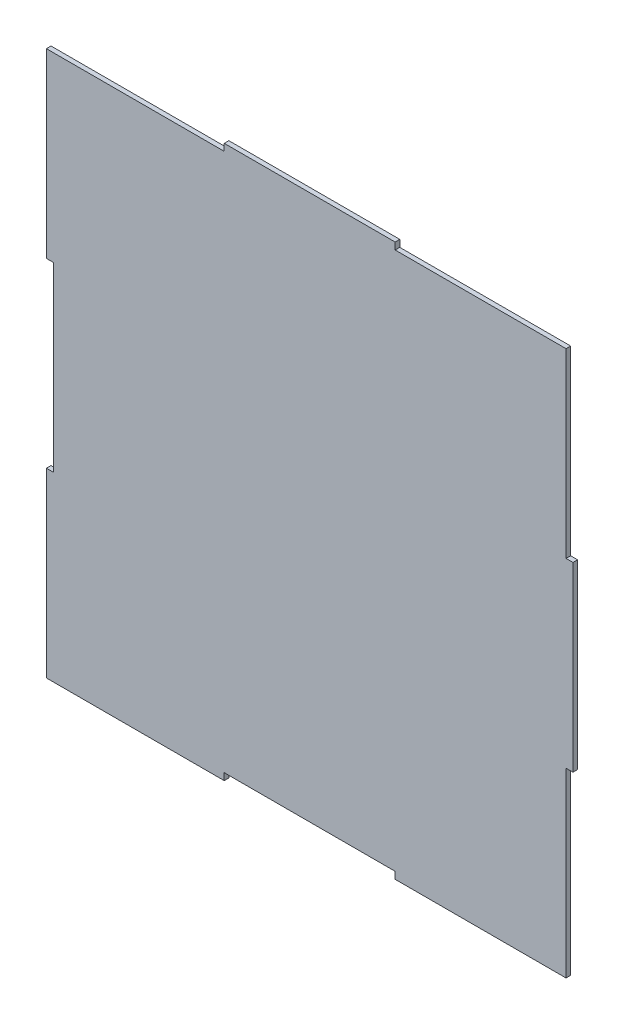
SolidWorks part; units mm, degrees
ref_plane "Front Plane" through (0, 0, 0) normal (0, 0, 1) x (1, 0, 0)
ref_plane "Top Plane" through (0, 0, 0) normal (0, 1, 0) x (1, 0, 0)
ref_plane "Right Plane" through (0, 0, 0) normal (1, 0, 0) x (0, 0, -1)
sketch "Sketch1" plane through (0, 0, 0) normal (0, 0, 1) x (1, 0, 0)
  line L0 (37, -118) -> (111, -118)
  line L1 (-111, -118) -> (-37, -118)
  line L2 (-111, -39.3333) -> (-111, 39.3333)
  line L3 (-111, 118) -> (-37, 118)
  line L4 (111, -118) -> (111, -39.3333)
  line L5 (-111, -118) -> (111, 118) construction
  line L6 (-111, 118) -> (111, -118) construction
  line L7 (-111, 118) -> (-114, 118)
  line L8 (111, 39.3333) -> (111, 118)
  line L9 (-37, -118) -> (-37, -115)
  line L10 (-37, -115) -> (37, -115)
  line L11 (37, -118) -> (37, -115)
  line L12 (111, -39.3333) -> (114, -39.3333)
  line L13 (37, 118) -> (111, 118)
  line L14 (111, 39.3333) -> (114, 39.3333)
  line L15 (114, -39.3333) -> (114, 39.3333)
  line L17 (-111, 39.3333) -> (-114, 39.3333)
  line L18 (-114, 118) -> (-114, 39.3333)
  line L19 (-111, -118) -> (-114, -118)
  line L21 (-111, -39.3333) -> (-114, -39.3333)
  line L22 (-114, -118) -> (-114, -39.3333)
  line L24 (-37, 118) -> (-37, 121)
  line L25 (-37, 121) -> (37, 121)
  line L26 (37, 118) -> (37, 121)
  dimension "D1" = 236
  dimension "D2" = 222
  dimension "D3" = 3
extrude "Boss-Extrude1" add sketch "Sketch1" along normal blind 2
equation "\"Resolution Projector X\"= 1920"
equation "\"Resolution Projector Y\"= 1080"
equation "\"Resolution Build\"= 0.1"
equation "\"Size Build Volume X\"= \"Resolution Projector X\" * \"Resolution Build\""
equation "\"Size Build Volume Y\"= 2 * \"Resolution Projector Y\" * \"Resolution Build\""
equation "\"Size Build Volume Z\"= \"Size Build Volume Y\""
equation "\"Thick\"= 0.125in"
equation "\"Size Enclosure Internal X\"= 350mm"
equation "\"Size Enclosure Internal Y\"= \"Size Enclosure Internal X\""
equation "\"Size Enclosure Internal Z\"= \"Size Enclosure Internal X\""
equation "\"Size Enclosure External Z\"= 1000mm"
equation "\"Diameter Screw\"= 3mm"
equation "\"Diameter Nut\"= 5.5mm"
equation "\"Thick Nut\"= 2.5mm"
equation "\"Length Screw\"= 12mm"
equation "\"D1@Sketch1\"=\"Size Build Volume Z\" + 20"
equation "\"D2@Sketch1\"=\"Size Build Volume X\" + 30"
